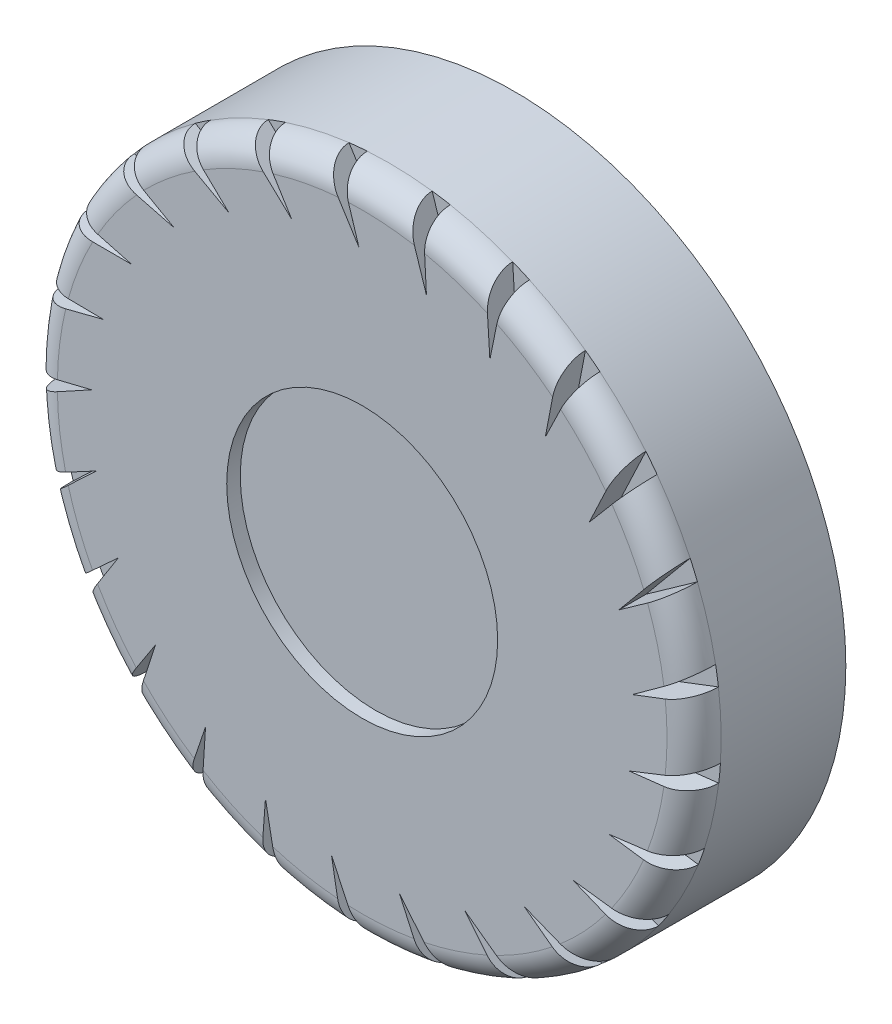
SolidWorks part; units mm, degrees
ref_plane "Front Plane" through (0, 0, 0) normal (0, 0, 1) x (1, 0, 0)
ref_plane "Top Plane" through (0, 0, 0) normal (0, 1, 0) x (1, 0, 0)
ref_plane "Right Plane" through (0, 0, 0) normal (1, 0, 0) x (0, 0, -1)
sketch "Sketch1" plane through (0, 0, 0) normal (0, 0, 1) x (1, 0, 0)
  circle A0 centre (-0.9371, 0.5073) radius 2.45
  dimension "D1" = 4.9
extrude "Boss-Extrude1" add sketch "Sketch1" along normal blind 1.12
fillet "Fillet1" radius 0.2 1 edges at (1.5129, 0.5073, 1.12)
sketch "Sketch2" plane through (0, 0, 0) normal (0, 0, -1) x (-1, 0, 0)
  circle A0 centre (0.9371, 0.5073) radius 0.51
  circle A1 centre (0.9371, 0.5073) radius 2.45 construction
  dimension "D1" = 0
  dimension "D2" = 1.02
extrude "Cut-Extrude2" cut sketch "Sketch2" against normal blind 0.03 contours A0
sketch "Sketch4" plane through (0, 0, 1.12) normal (0, 0, 1) x (1, 0, 0)
  line L0 (-1.9474, 4.0654) -> (-1.4474, 4.0654)
  line L1 (-1.4474, 4.0654) -> (-0.9611, 2.5073)
  line L2 (-0.9611, 2.5073) -> (-1.9474, 4.0654)
  circle A0 centre (-0.9371, 0.5073) radius 2.25 construction
  dimension "D1" = 0.5
  dimension "D2" = 15
  dimension "D3" = 2
extrude "Cut-Extrude4" cut sketch "Sketch4" against normal blind 0.2
pattern_circular "CirPattern1" count 25 over 360 about axis through (-0.9371, 0.5073, 0) along (0, 0, 1) of "Cut-Extrude4"
sketch "Sketch5" plane through (0, 0, 1.12) normal (0, 0, 1) x (1, 0, 0)
  circle A0 centre (-0.9371, 0.5073) radius 1
  circle A1 centre (-0.9371, 0.5073) radius 2.45 construction
  dimension "D1" = 0
  dimension "D2" = 2
extrude "Cut-Extrude5" cut sketch "Sketch5" against normal blind 0.1
